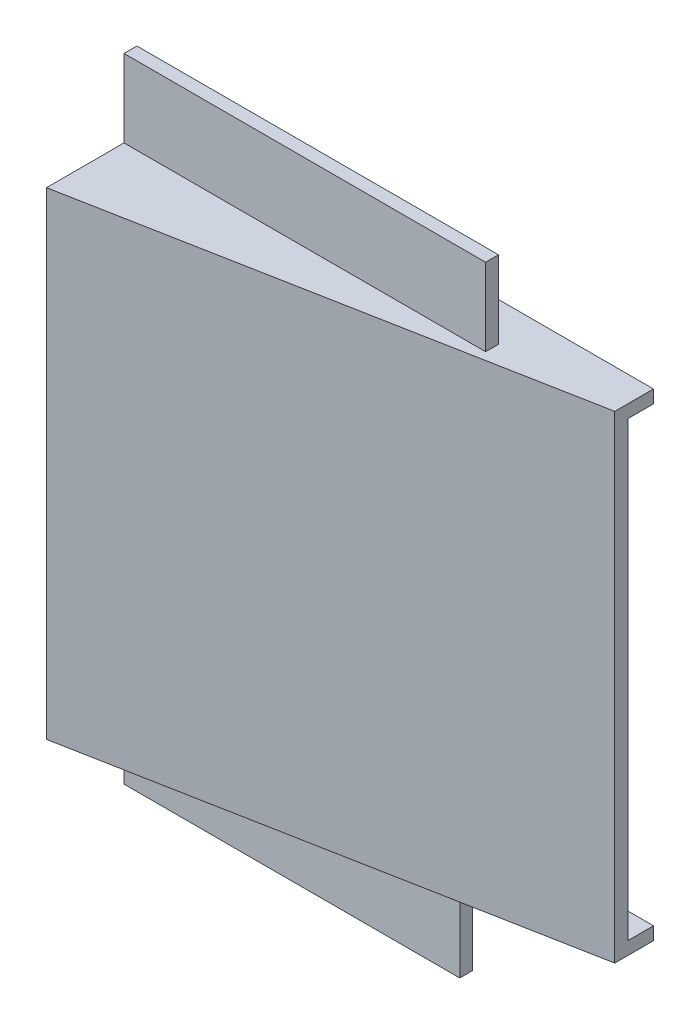
SolidWorks part; units mm, degrees
material "Balsa"
ref_plane "Front Plane" through (0, 0, 0) normal (0, 0, 1) x (1, 0, 0)
ref_plane "Top Plane" through (0, 0, 0) normal (0, 1, 0) x (1, 0, 0)
ref_plane "Right Plane" through (0, 0, 0) normal (1, 0, 0) x (0, 0, -1)
sketch "Sketch1" plane through (0, 0, 0) normal (0, 0, 1) x (1, 0, 0)
  line L1 (0, 0) -> (185, 0)
  line L2 (0, 0) -> (0, -185)
  line L3 (0, -185) -> (185, -185)
  line L4 (185, 0) -> (185, -185)
  dimension "D1" = 185
  dimension "D2" = 185
extrude "Boss-Extrude1" add sketch "Sketch1" along normal blind 50
sketch "Sketch8" plane through (0, -185, 0) normal (0, -1, 0) x (1, 0, 0)
  line L0 (0, 50) -> (185, 15)
  line L1 (185, 50) -> (185, 0) construction
  line L2 (185, 15) -> (185, 50)
  line L3 (185, 50) -> (0, 50)
  dimension "D1" = 15
extrude "Cut-Extrude1" cut sketch "Sketch8" against normal blind 190
sketch "Sketch9" plane through (0, -185, 0) normal (0, -1, 0) x (1, 0, 0)
  line L0 (185, 9.9113) -> (5, 43.9654)
  line L1 (5, 43.9654) -> (5, 0)
  line L2 (0, 0) -> (185, 0) construction
  line L3 (0, 50) -> (0, 0) construction
  line L4 (185, 15) -> (185, 0) construction
  line L5 (0, 50) -> (185, 15) construction
  line L6 (5, 0) -> (185, 0)
  line L7 (185, 0) -> (185, 9.9113)
  dimension "D1" = 5
  dimension "D2" = 5
  dimension "D3" = 5
extrude "Cut-Extrude3" cut sketch "Sketch9" against normal blind 175 from offset 5 offset against normal yes
sketch "Sketch10" plane through (0, -185, 0) normal (0, -1, 0) x (1, 0, 0)
  line L0 (0, 50) -> (0, 0) construction
  line L1 (0, 20) -> (130, 20)
  line L2 (0, 20) -> (0, 15)
  line L3 (0, 15) -> (130, 15)
  line L4 (130, 20) -> (130, 15)
  line L5 (0, 0) -> (185, 0) construction
  dimension "D1" = 15
  dimension "D2" = 5
  dimension "D3" = 130
extrude "Boss-Extrude2" add sketch "Sketch10" along normal blind 30
sketch "Sketch11" plane through (0, 0, 0) normal (0, 1, 0) x (1, 0, 0)
  line L5 (0, -50) -> (0, 0) construction
  line L6 (0, -15) -> (140, -15)
  line L7 (0, -15) -> (0, -20)
  line L8 (0, -20) -> (140, -20)
  line L9 (140, -15) -> (140, -20)
  line L10 (185, 0) -> (0, 0) construction
  dimension "D1" = 15
  dimension "D2" = 5
  dimension "D3" = 140
extrude "Boss-Extrude3" add sketch "Sketch11" along normal blind 30
